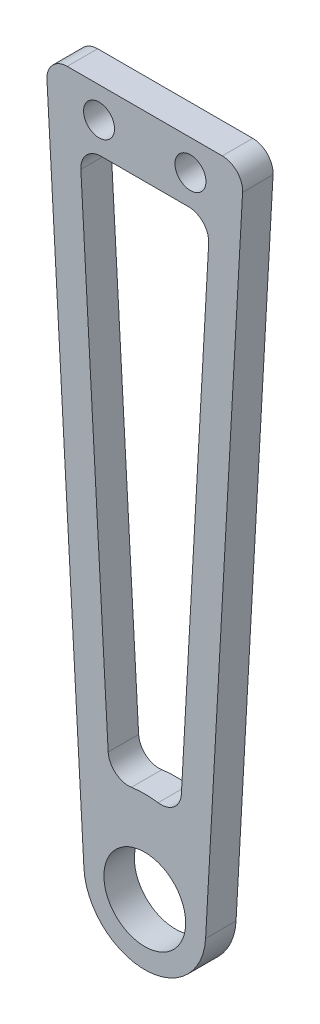
SolidWorks part; units mm, degrees
material "Thornel Mat VMA"
ref_plane "前视基准面" through (0, 0, 0) normal (0, 0, 1) x (1, 0, 0)
ref_plane "上视基准面" through (0, 0, 0) normal (0, 1, 0) x (1, 0, 0)
ref_plane "右视基准面" through (0, 0, 0) normal (1, 0, 0) x (0, 0, -1)
sketch "草图1" plane through (0, 0, 0) normal (0, 0, 1) x (1, 0, 0)
  line L0 (0, 0) -> (0, -90) construction
  line L1 (-10.983, -0.6111) -> (-5.9907, -90.3333)
  line L2 (10.983, -0.6111) -> (5.9907, -90.3333)
  line L3 (-7.4184, -10.6756) -> (-3.4668, -81.6945)
  line L4 (7.4184, -10.6756) -> (3.4668, -81.6945)
  circle A0 centre (0, 0) radius 11
  circle A1 centre (0, -90) radius 6
  circle A2 centre (0, 0) radius 5.5 construction
  circle A3 centre (5.5, 0) radius 1.01
  circle A4 centre (-2.75, -4.7631) radius 1.01
  circle A5 centre (-2.75, 4.7631) radius 1.01
  circle A6 centre (0, 0) radius 3.5
  circle A7 centre (0, -90) radius 4.025
  arc A8 (-7.4184, -10.6756) -> (7.4184, -10.6756) centre (0, 0) ccw
  arc A10 (3.4668, -81.6945) -> (-3.4668, -81.6945) centre (0, -90) ccw
  point P14 (0, 0)
  dimension "D1" = 22
  dimension "D2" = 11
  dimension "D3" = 2.02
  dimension "D5" = 7
  dimension "D6" = 12
  dimension "D7" = 8.05
  dimension "D10" = 2
  dimension "D11" = 9
  dimension "D8" = 90
  dimension "D9" = 3
  dimension "D4" = 3
extrude "凸台-拉伸1" add sketch "草图1" along normal blind 3 contours A1 L2 A0 L1 L4 A10 L3 A8 | A0 A6 A5 A4 A3 | A1 A7
sketch "草图2" plane through (0, 0, 3) normal (0, 0, 1) x (1, 0, 0)
  line L0 (-6.7452, -22.7747) -> (6.7452, -22.7747)
  line L1 (-7.4184, -10.6756) -> (-3.4668, -81.6945) construction
  line L2 (7.4184, -10.6756) -> (3.4668, -81.6945) construction
  line L3 (-6.4113, -28.7747) -> (6.4113, -28.7747)
  line L4 (0, 0) -> (0, -50000) construction
  line L5 (-6.7452, -22.7747) -> (-6.4113, -28.7747)
  line L6 (6.7452, -22.7747) -> (6.4113, -28.7747)
  circle A0 centre (-4.5, -25.7747) radius 1.525
  circle A2 centre (4.5, -25.7747) radius 1.525
  dimension "D1" = 3.05
  dimension "D3" = 3
  dimension "D2" = 9
  dimension "D4" = 3
extrude "凸台-拉伸2" add sketch "草图2" against normal up to surface (3 mm away) up to face at (0, -43.9861, 0)
sketch "草图3" plane through (0, 0, 3) normal (0, 0, 1) x (1, 0, 0)
  line L0 (-12.1126, -22.7747) -> (12.4405, -22.7747)
  line L1 (12.4405, -22.7747) -> (12.4405, 13.8022)
  line L2 (12.4405, 13.8022) -> (-12.1126, 13.8022)
  line L3 (-12.1126, 13.8022) -> (-12.1126, -22.7747)
extrude "切除-拉伸1" cut sketch "草图3" against normal blind 10
fillet "圆角1" radius 2 6 edges at (-3.4668, -81.6945, 1.5) (3.4668, -81.6945, 1.5) (-6.4113, -28.7747, 1.5) (6.4113, -28.7747, 1.5) (9.7498, -22.7747, 1.5) (-9.7498, -22.7747, 1.5)
